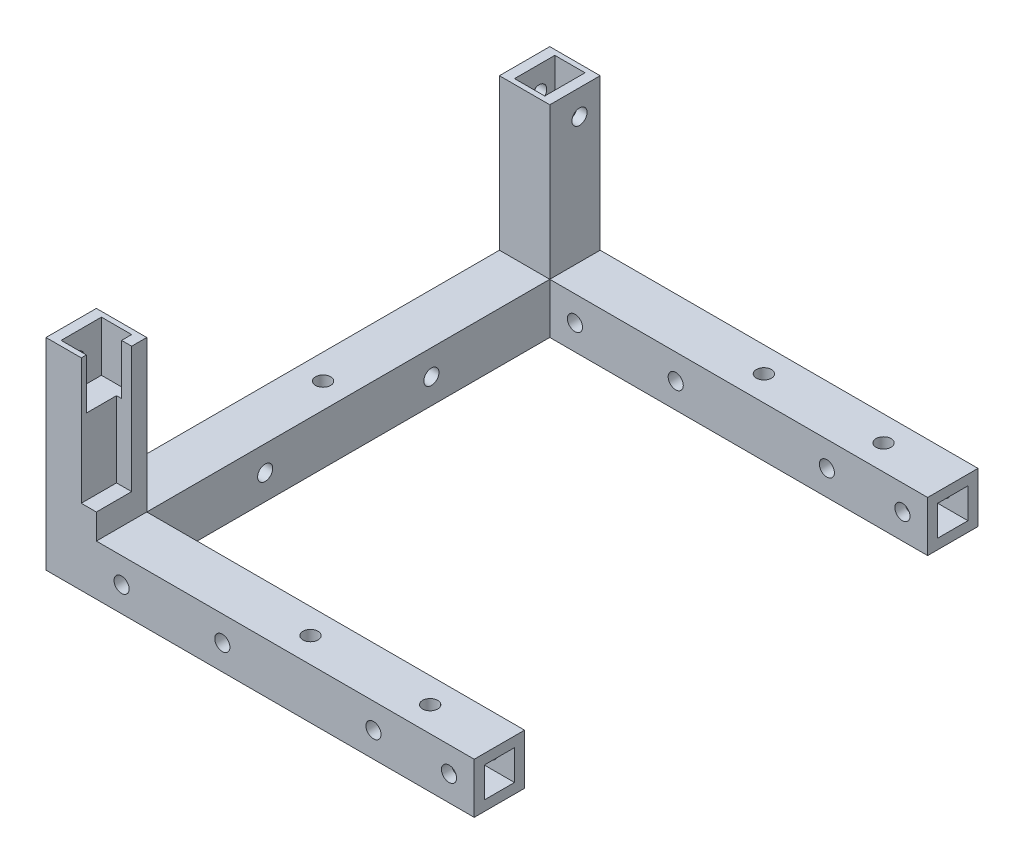
SolidWorks part; units mm, degrees
ref_plane "Front Plane" through (0, 0, 0) normal (0, 0, 1) x (1, 0, 0)
ref_plane "Top Plane" through (0, 0, 0) normal (0, 1, 0) x (1, 0, 0)
ref_plane "Right Plane" through (0, 0, 0) normal (1, 0, 0) x (0, 0, -1)
sketch "Sketch1" plane through (0, 0, 0) normal (0, 1, 0) x (1, 0, 0)
  line L0 (0, 0) -> (0, 200)
  line L1 (0, 200) -> (320, 200)
  line L2 (320, 200) -> (320, 0)
  line L3 (320, 0) -> (0, 0)
  line L4 (300, 20) -> (20, 20)
  line L5 (20, 20) -> (20, 180)
  line L6 (20, 180) -> (300, 180)
  line L7 (300, 180) -> (300, 20)
  dimension "D1" = 280
  dimension "D2" = 320
  dimension "D3" = 200
  dimension "D4" = 160
  dimension "D5" = 20
  dimension "D6" = 20
extrude "Boss-Extrude1" add sketch "Sketch1" along normal blind 20
sketch "Sketch2" plane through (0, 20, 0) normal (0, 1, 0) x (1, 0, 0)
  line L6 (320, 200) -> (0, 200) construction
  line L7 (320, 0) -> (170, 0)
  line L8 (320, 0) -> (320, 200)
  line L9 (320, 200) -> (170, 200)
  line L10 (170, 0) -> (170, 200)
  dimension "D1" = 150
extrude "Cut-Extrude1" cut sketch "Sketch2" against normal blind 20
sketch "Sketch3" plane through (0, 20, 0) normal (0, 1, 0) x (1, 0, 0)
  line L0 (0, 100) -> (195.6519, 100) construction
  line L1 (0, 0) -> (20, 0)
  line L2 (0, 0) -> (0, 20)
  line L3 (0, 20) -> (20, 20)
  line L4 (20, 0) -> (20, 20)
  line L5 (0, 200) -> (0, 0) construction
  line L6 (0, 180) -> (20, 180)
  line L7 (20, 200) -> (20, 180)
  line L8 (0, 200) -> (20, 200)
  line L9 (0, 200) -> (0, 180)
extrude "Boss-Extrude2" add sketch "Sketch3" along normal blind 60
sketch "Sketch4" plane through (0, 80, 0) normal (0, 1, 0) x (1, 0, 0)
  line L0 (0, 20) -> (0, 0) construction
  line L1 (4, 18) -> (16, 18)
  line L2 (4, 18) -> (4, 2)
  line L3 (4, 2) -> (16, 2)
  line L4 (16, 18) -> (16, 2)
  line L5 (20, 20) -> (0, 20) construction
  line L6 (20, 20) -> (20, 180) construction
  line L7 (20, 180) -> (20, 100) construction
  line L8 (20, 100) -> (87.8571, 100) construction
  line L9 (4, 198) -> (16, 198)
  line L10 (16, 182) -> (16, 198)
  line L11 (4, 182) -> (16, 182)
  line L12 (4, 182) -> (4, 198)
  dimension "D1" = 16
  dimension "D2" = 12
  dimension "D3" = 4
  dimension "D4" = 2
extrude "Cut-Extrude2" cut sketch "Sketch4" against normal blind 20
sketch "Sketch5" plane through (170, 0, 0) normal (1, 0, 0) x (0, 0, -1)
  line L0 (20, 0) -> (0, 0) construction
  line L1 (16, 4) -> (4, 4)
  line L2 (16, 4) -> (16, 16)
  line L3 (16, 16) -> (4, 16)
  line L4 (4, 4) -> (4, 16)
  line L5 (0, 0) -> (0, 20) construction
  line L6 (180, 0) -> (20, 0) construction
  line L7 (20, 0) -> (100, 0) construction
  line L8 (100, 0) -> (100, 76.0608) construction
  line L9 (184, 16) -> (196, 16)
  line L10 (196, 4) -> (196, 16)
  line L11 (184, 4) -> (196, 4)
  line L12 (184, 4) -> (184, 16)
  dimension "D1" = 4
  dimension "D2" = 4
  dimension "D3" = 12
  dimension "D4" = 12
extrude "Cut-Extrude3" cut sketch "Sketch5" against normal blind 22
sketch "Sketch8" plane through (0, 0, -200) normal (0, 0, -1) x (-1, 0, 0)
  line L1 (-170, 0) -> (0, 0) construction
  line L3 (0, 80) -> (0, 0) construction
  circle A0 centre (-30, 10) radius 3
  circle A1 centre (-160, 10) radius 3
  circle A2 centre (-70, 10) radius 3
  circle A3 centre (-130, 10) radius 3
  dimension "D2" = 10
  dimension "D3" = 6
  dimension "D4" = 6
  dimension "D5" = 10
  dimension "D6" = 160
  dimension "D7" = 6
  dimension "D8" = 6
  dimension "D9" = 10
  dimension "D10" = 10
  dimension "D11" = 130
  dimension "D1" = 30
  dimension "D12" = 70
extrude "Cut-Extrude5" cut sketch "Sketch8" against normal through all both and the other way through all
sketch "Sketch10" plane through (0, 0, 0) normal (0, -1, 0) x (1, 0, 0)
  line L0 (170, -20) -> (170, 0) construction
  line L1 (0, 0) -> (170, 0) construction
  line L2 (0, -100) -> (189.0588, -100) construction
  line L3 (0, -200) -> (0, 0) construction
  circle A0 centre (142.5, -10) radius 3
  circle A1 centre (95, -10) radius 3
  circle A2 centre (10, -100) radius 3
  circle A3 centre (142.5, -190) radius 3
  circle A4 centre (95, -190) radius 3
  dimension "D1" = 75
  dimension "D2" = 27.5
  dimension "D3" = 6
  dimension "D4" = 6
  dimension "D5" = 10
  dimension "D6" = 10
  dimension "D7" = 6
  dimension "D8" = 10
  dimension "D9" = 95
  dimension "D10" = 142.5
extrude "Cut-Extrude6" cut sketch "Sketch10" against normal blind 30
sketch "Sketch11" plane through (20, 0, 0) normal (1, 0, 0) x (0, 0, -1)
  line L1 (0, 80) -> (14, 80)
  line L2 (0, 80) -> (0, 30)
  line L3 (0, 30) -> (14, 30)
  line L4 (14, 80) -> (14, 30)
  dimension "D1" = 14
  dimension "D2" = 50
extrude "Cut-Extrude7" cut sketch "Sketch11" against normal blind 6
sketch "Sketch12" plane through (0, 0, 0) normal (-1, 0, 0) x (0, 0, 1)
  line L0 (-200, 80) -> (-200, 0) construction
  line L1 (0, 80) -> (0, 0) construction
  line L2 (-200, 0) -> (0, 0) construction
  circle A0 centre (-133, 10) radius 3
  circle A1 centre (-67, 10) radius 3
  dimension "D1" = 67
  dimension "D2" = 67
  dimension "D3" = 6
  dimension "D4" = 6
  dimension "D5" = 10
  dimension "D6" = 10
extrude "Cut-Extrude8" cut sketch "Sketch12" against normal blind 26
sketch "Sketch13" plane through (0, 0, 0) normal (-1, 0, 0) x (0, 0, 1)
  line L0 (-200, 80) -> (-180, 80) construction
  line L1 (-20, 80) -> (0, 80) construction
  line L2 (-200, 80) -> (-200, 0) construction
  line L3 (0, 80) -> (0, 0) construction
  circle A0 centre (-191.8, 70) radius 3
  circle A1 centre (-8.2, 70) radius 3
  dimension "D1" = 10
  dimension "D2" = 10
  dimension "D3" = 8.2
  dimension "D4" = 8.2
  dimension "D5" = 6
  dimension "D6" = 6
extrude "Cut-Extrude9" cut sketch "Sketch13" against normal blind 26 contours A0 | A1
